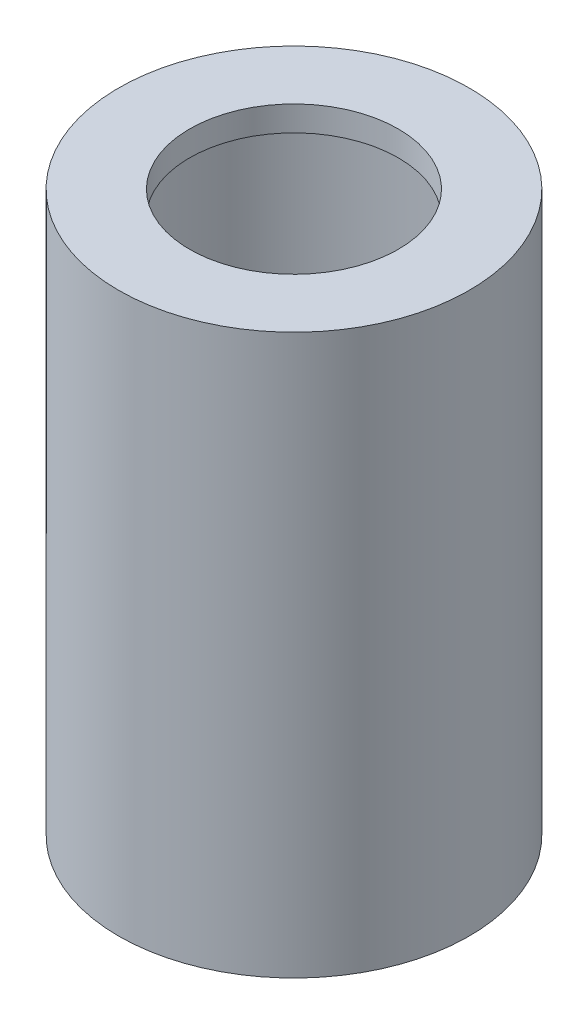
SolidWorks part; units mm, degrees
ref_plane "Front Plane" through (0, 0, 0) normal (0, 0, 1) x (1, 0, 0)
ref_plane "Top Plane" through (0, 0, 0) normal (0, 1, 0) x (1, 0, 0)
ref_plane "Right Plane" through (0, 0, 0) normal (1, 0, 0) x (0, 0, -1)
sketch "Sketch1" plane through (0, 0, 0) normal (0, 1, 0) x (1, 0, 0)
  circle A0 centre (0, 0) radius 26.67
  dimension "D1" = 53.34
extrude "Boss-Extrude1" add sketch "Sketch1" along normal blind 81.28
shell "Shell1" thickness 2.54
sketch "Sketch2" plane through (0, 81.28, 0) normal (0, 1, 0) x (1, 0, 0)
  circle A0 centre (0, 0) radius 15.875
  circle A1 centre (0, 0) radius 26.67 construction
  circle A2 centre (0, 0) radius 26.67
  dimension "D1" = 31.75
extrude "Boss-Extrude2" add sketch "Sketch2" along normal blind 3.81
